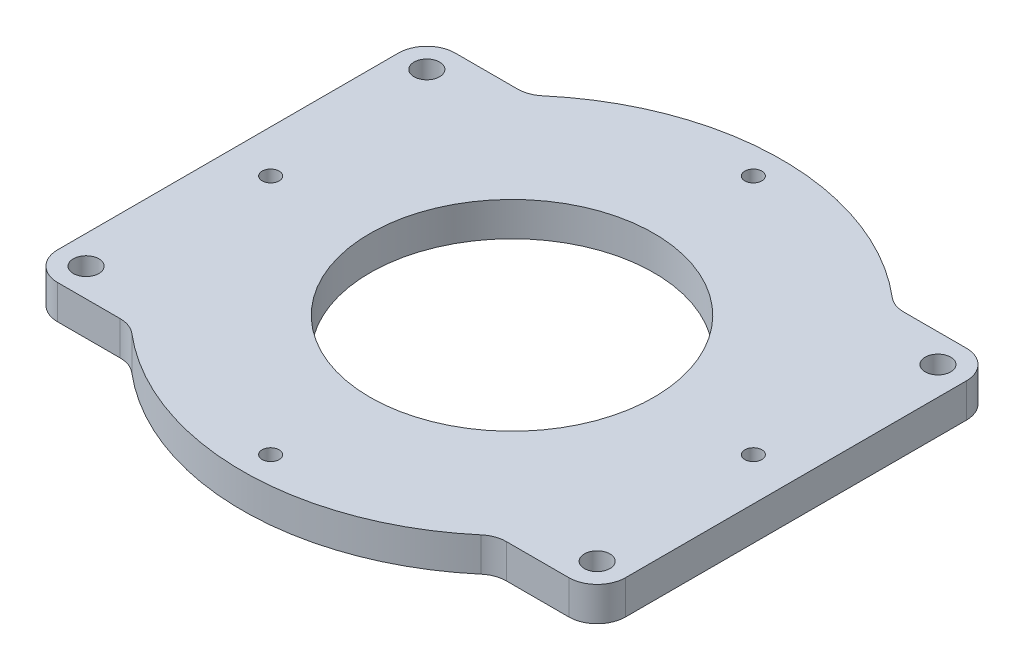
SolidWorks part; units mm, degrees
ref_plane "Front Plane" through (0, 0, 0) normal (0, 0, 1) x (1, 0, 0)
ref_plane "Top Plane" through (0, 0, 0) normal (0, 1, 0) x (1, 0, 0)
ref_plane "Right Plane" through (0, 0, 0) normal (1, 0, 0) x (0, 0, -1)
sketch "Sketch1" plane through (0, 0, 0) normal (0, 1, 0) x (1, 0, 0)
  line L0 (0, 0) -> (0, 42.5) construction
  line L1 (45, -30) -> (-45, -30) construction
  line L2 (45, -30) -> (45, 30) construction
  line L3 (45, 30) -> (-45, 30) construction
  line L4 (-45, -30) -> (-45, 30) construction
  line L5 (45, -30) -> (-45, 30) construction
  line L6 (45, 30) -> (-45, -30) construction
  line L7 (45, -35) -> (-45, -35) construction
  line L8 (50, -30) -> (50, 30)
  line L9 (45, 35) -> (-45, 35) construction
  line L10 (-50, -30) -> (-50, 30)
  line L11 (50, -35) -> (-50, 35) construction
  line L12 (50, 35) -> (-50, -35) construction
  line L13 (0, 0) -> (42.5, 0) construction
  line L14 (-45, 35) -> (-34.0037, 35)
  line L15 (34.0037, 35) -> (45, 35)
  line L16 (34.0037, -35) -> (45, -35)
  line L17 (-45, -35) -> (-34.0037, -35)
  circle A0 centre (-45, 30) radius 2.25
  circle A1 centre (-45, -30) radius 2.25
  circle A2 centre (45, -30) radius 2.25
  circle A3 centre (45, 30) radius 2.25
  circle A4 centre (0, 0) radius 25
  arc A5 (-50, -30) -> (-45, -35) centre (-45, -30) ccw
  arc A6 (45, -35) -> (50, -30) centre (45, -30) ccw
  arc A7 (50, 30) -> (45, 35) centre (45, 30) ccw
  arc A8 (-45, 35) -> (-50, 30) centre (-45, 30) ccw
  circle A9 centre (0, 0) radius 42.5 construction
  circle A10 centre (0, 42.5) radius 1.5
  circle A11 centre (42.5, 0) radius 1.5
  circle A12 centre (0, -42.5) radius 1.5
  circle A13 centre (-42.5, 0) radius 1.5
  arc A14 (30.7652, 36.1905) -> (-30.7652, 36.1905) centre (0, 0) ccw
  arc A15 (34.0037, 35) -> (30.7652, 36.1905) centre (34.0037, 40) cw
  arc A16 (-30.7652, 36.1905) -> (-34.0037, 35) centre (-34.0037, 40) cw
  arc A17 (34.0037, -35) -> (30.7652, -36.1905) centre (34.0037, -40) ccw
  arc A18 (30.7652, -36.1905) -> (-30.7652, -36.1905) centre (0, 0) cw
  arc A19 (-30.7652, -36.1905) -> (-34.0037, -35) centre (-34.0037, -40) ccw
  point P0 (0, 0)
  point P41 (32.1131, 35)
  point P44 (-32.1131, 35)
  dimension "D1" = 4.5
  dimension "D4" = 50
  dimension "D7" = 5
  dimension "D8" = 85
  dimension "D9" = 3
  dimension "D10" = 5
  dimension "D11" = 5
  dimension "D2" = 90
  dimension "D3" = 60
  dimension "D5" = 5
  dimension "D6" = 5
extrude "Boss-Extrude1" add sketch "Sketch1" along normal blind 6
